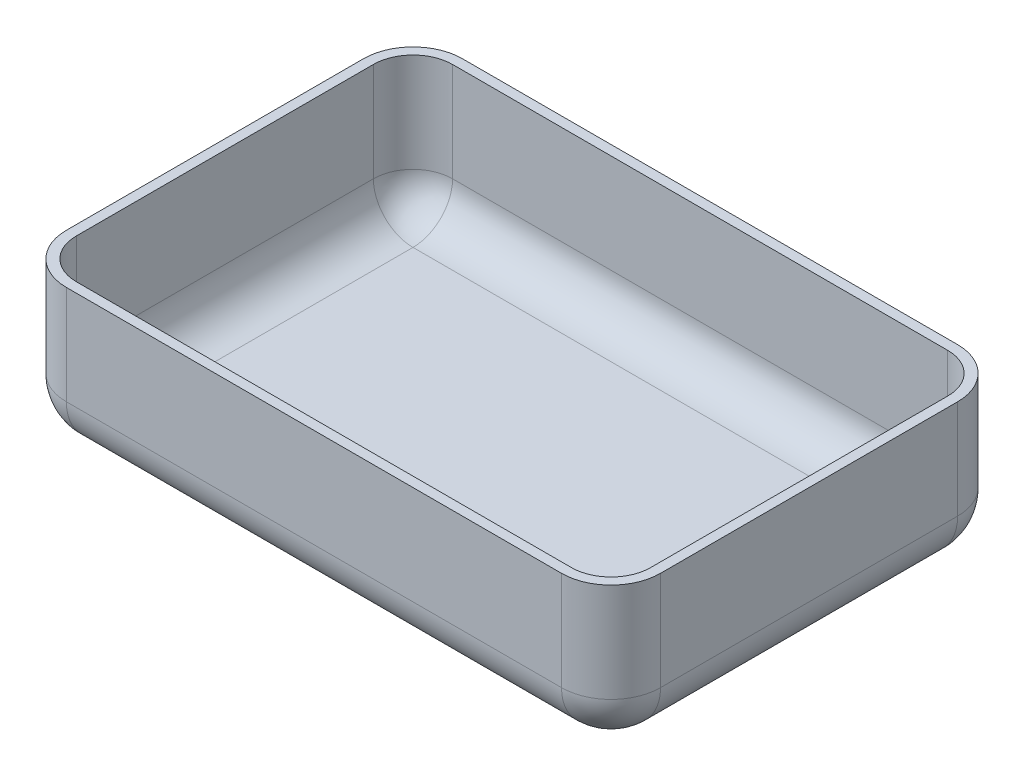
SolidWorks part; units mm, degrees
ref_plane "Front Plane" through (0, 0, 0) normal (0, 0, 1) x (1, 0, 0)
ref_plane "Top Plane" through (0, 0, 0) normal (0, 1, 0) x (1, 0, 0)
ref_plane "Right Plane" through (0, 0, 0) normal (1, 0, 0) x (0, 0, -1)
sketch "Croquis1" plane through (0, 0, 0) normal (0, 1, 0) x (1, 0, 0)
  line L1 (76.2, -50.8) -> (-76.2, -50.8)
  line L2 (76.2, -50.8) -> (76.2, 50.8)
  line L3 (76.2, 50.8) -> (-76.2, 50.8)
  line L4 (-76.2, -50.8) -> (-76.2, 50.8)
  line L5 (76.2, -50.8) -> (-76.2, 50.8) construction
  line L6 (76.2, 50.8) -> (-76.2, -50.8) construction
  point P0 (0, 0)
  dimension "D1" = 152.4
  dimension "D2" = 101.6
extrude "Saliente-Extruir1" add sketch "Croquis1" along normal blind 38.1
fillet "Redondeo1" radius 12.7 8 edges at (-76.2, 0, 0) (0, 0, -50.8) (76.2, 0, 0) (0, 0, 50.8) (-76.2, 19.05, -50.8) (76.2, 19.05, -50.8) (76.2, 19.05, 50.8) (-76.2, 19.05, 50.8)
shell "Vaciado1" thickness 2.54
